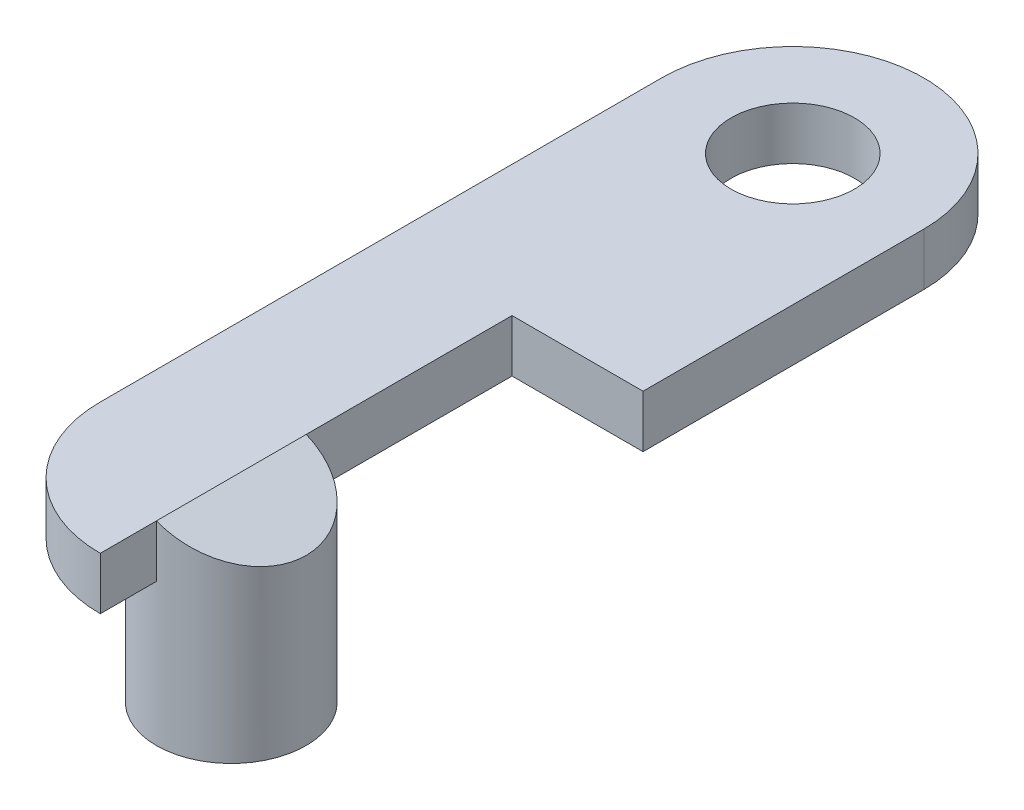
SolidWorks part; units mm, degrees
ref_plane "前视基准面" through (0, 0, 0) normal (0, 0, 1) x (1, 0, 0)
ref_plane "上视基准面" through (0, 0, 0) normal (0, 1, 0) x (1, 0, 0)
ref_plane "右视基准面" through (0, 0, 0) normal (1, 0, 0) x (0, 0, -1)
sketch "草图1" plane through (0, 0, 0) normal (0, 1, 0) x (1, 0, 0)
  circle A0 centre (0, 0) radius 2
  dimension "D1" = 4
extrude "凸台-拉伸1" add sketch "草图1" along normal blind 3.8
sketch "草图2" plane through (0, 3.8, 0) normal (0, 1, 0) x (1, 0, 0)
  line L5 (0, 0) -> (0, 15) construction
  line L6 (-3.5, 0) -> (-3.5, 15)
  line L7 (3.5, 0) -> (3.5, 15)
  circle A2 centre (0, 15) radius 1.65
  arc A3 (-3.5, 0) -> (3.5, 0) centre (0, 0) ccw
  arc A4 (3.5, 15) -> (-3.5, 15) centre (0, 15) ccw
  point P3 (0, 7.5)
  dimension "D1" = 3.3
  dimension "D3" = 3.5
  dimension "D2" = 15
extrude "凸台-拉伸2" add sketch "草图2" along normal blind 1.4
sketch "草图3" plane through (0, 3.8, 0) normal (0, -1, 0) x (1, 0, 0)
  line L0 (0, 3.5) -> (0, 2)
  line L1 (0, -2) -> (0, -7.5)
  line L2 (0, -7.5) -> (3.5, -7.5)
  line L3 (3.5, 0) -> (3.5, -15) construction
  line L4 (3.5, 0) -> (3.5, -7.5)
  arc A0 (3.5, 0) -> (-3.5, 0) centre (0, 0) ccw construction
  circle A1 centre (0, 0) radius 2
  arc A2 (0, -2) -> (0, 2) centre (0, 0) ccw
  arc A3 (3.5, 0) -> (0, 3.5) centre (0, 0) ccw
  dimension "D1" = 0
extrude "切除-拉伸1" cut sketch "草图3" against normal through all
sketch "草图4" plane through (0, 0, -7.5) normal (0, 0, 1) x (1, 0, 0)
  line L0 (0, 5.2) -> (3.5, 3.8)
  line L1 (3.5, 3.8) -> (3.5, 5.2)
  line L2 (3.5, 5.2) -> (0, 5.2)
extrude "切除-拉伸2" cut sketch "草图4" along normal through all
